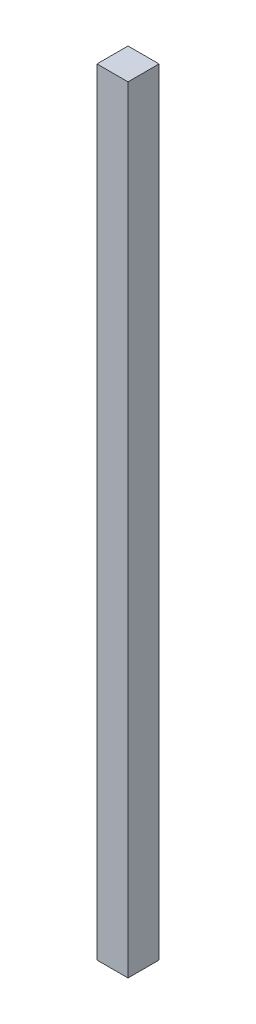
SolidWorks part; units mm, degrees
ref_plane "前视基准面" through (0, 0, 0) normal (0, 0, 1) x (1, 0, 0)
ref_plane "上视基准面" through (0, 0, 0) normal (0, 1, 0) x (1, 0, 0)
ref_plane "右视基准面" through (0, 0, 0) normal (1, 0, 0) x (0, 0, -1)
sketch "Sketch1" plane through (0, 0, 0) normal (0, 1, 0) x (1, 0, 0)
  line L1 (-10, 10) -> (10, 10)
  line L2 (-10, 10) -> (-10, -10)
  line L3 (-10, -10) -> (10, -10)
  line L4 (10, 10) -> (10, -10)
  line L5 (-10, 10) -> (10, -10) construction
  line L6 (-10, -10) -> (10, 10) construction
  point P0 (0, 0)
  dimension "D1" = 20
  dimension "D2" = 20
extrude "Boss-Extrude1" add sketch "Sketch1" along normal blind 500
